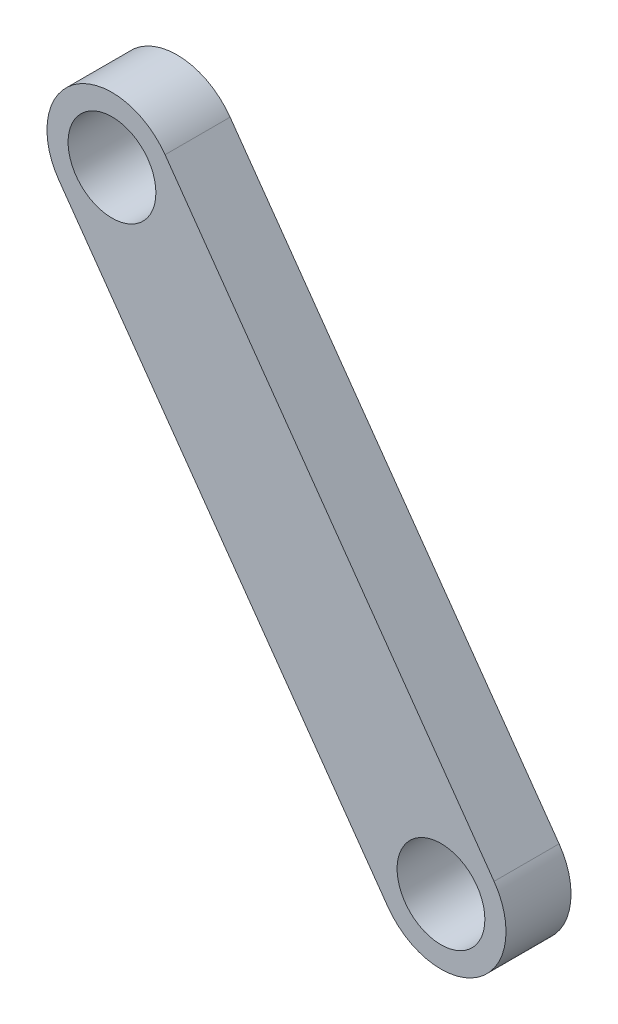
SolidWorks part; units mm, degrees
ref_plane "Front Plane" through (0, 0, 0) normal (0, 0, 1) x (1, 0, 0)
ref_plane "Top Plane" through (0, 0, 0) normal (0, 1, 0) x (1, 0, 0)
ref_plane "Right Plane" through (0, 0, 0) normal (1, 0, 0) x (0, 0, -1)
sketch "Sketch1" plane through (0, 0, 0) normal (0, 0, 1) x (1, 0, 0)
  line L1 (-16.9728, 30.9025) -> (3.2649, 2.311)
  line L2 (-3.2649, -2.311) -> (-23.5025, 26.2806)
  circle A0 centre (0, 0) radius 2.7
  circle A1 centre (-20.2376, 28.5916) radius 2.7
  arc A2 (-3.2649, -2.311) -> (3.2649, 2.311) centre (0, 0) ccw
  arc A3 (-16.9728, 30.9025) -> (-23.5025, 26.2806) centre (-20.2376, 28.5916) ccw
  dimension "D1" = 8
  dimension "D2" = 5.4
  dimension "D3" = 35.0291
extrude "Boss-Extrude1" add sketch "Sketch1" along normal blind 4
